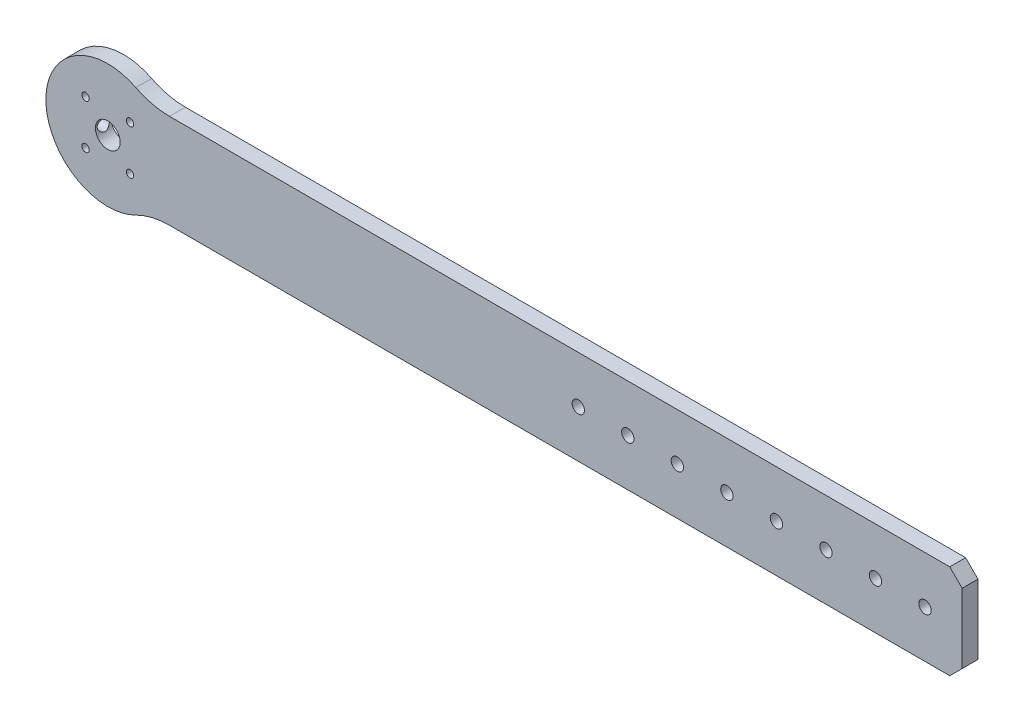
SolidWorks part; units mm, degrees
material "7075-T6, Plate (SS)"
ref_plane "Front Plane" through (0, 0, 0) normal (0, 0, 1) x (1, 0, 0)
ref_plane "Top Plane" through (0, 0, 0) normal (0, 1, 0) x (1, 0, 0)
ref_plane "Right Plane" through (0, 0, 0) normal (1, 0, 0) x (0, 0, -1)
sketch "Sketch1" plane through (0, 0, 0) normal (0, 0, 1) x (1, 0, 0)
  line L0 (0, 0) -> (345, 0) construction
  line L1 (0, 0) -> (8.9803, 8.9803) construction
  line L2 (345, 19.05) -> (16.1894, 19.05)
  line L3 (345, 19.05) -> (345, -19.05)
  line L4 (345, -19.05) -> (16.1894, -19.05)
  arc A0 (16.1894, 19.05) -> (16.1894, -19.05) centre (0, 0) ccw
  circle A1 centre (0, 0) radius 12.7 construction
  circle A3 centre (8.9803, 8.9803) radius 1.5
  circle A6 centre (0, 0) radius 5
  circle A7 centre (330, 0) radius 2.5
  circle A8 centre (310, 0) radius 2.5
  circle A9 centre (290, 0) radius 2.5
  circle A10 centre (270, 0) radius 2.5
  circle A11 centre (250, 0) radius 2.5
  circle A12 centre (230, 0) radius 2.5
  circle A13 centre (210, 0) radius 2.5
  circle A14 centre (190, 0) radius 2.5
  circle A15 centre (8.9803, -8.9803) radius 1.5
  circle A16 centre (-8.9803, -8.9803) radius 1.5
  circle A17 centre (-8.9803, 8.9803) radius 1.5
  point P35 (0, 0)
  dimension "D1" = 50
  dimension "D4" = 25.4
  dimension "D5" = 45
  dimension "D6" = 10
  dimension "D7" = 5
  dimension "D11" = 3
  dimension "D2" = 345
  dimension "D3" = 38.1
  dimension "D8" = 15
  dimension "D10" = 20
  dimension "D9" = 8
  dimension "D12" = 4
extrude "Boss-Extrude1" add sketch "Sketch1" along normal mid plane 6.4
fillet "Fillet1" radius 30 2 edges at (16.1894, -19.05, 0) (16.1894, 19.05, 0)
chamfer "Chamfer1" distance 5 angle 45 2 edges at (345, -19.05, 0) (345, 19.05, 0)
sketch "Sketch3" plane through (0, 0, 0) normal (1, 0, 0) x (0, 0, -1)
  circle A0 centre (0, 0) radius 2.5
  dimension "D1" = 5
extrude "Cut-Extrude1" cut sketch "Sketch3" against normal up to next
